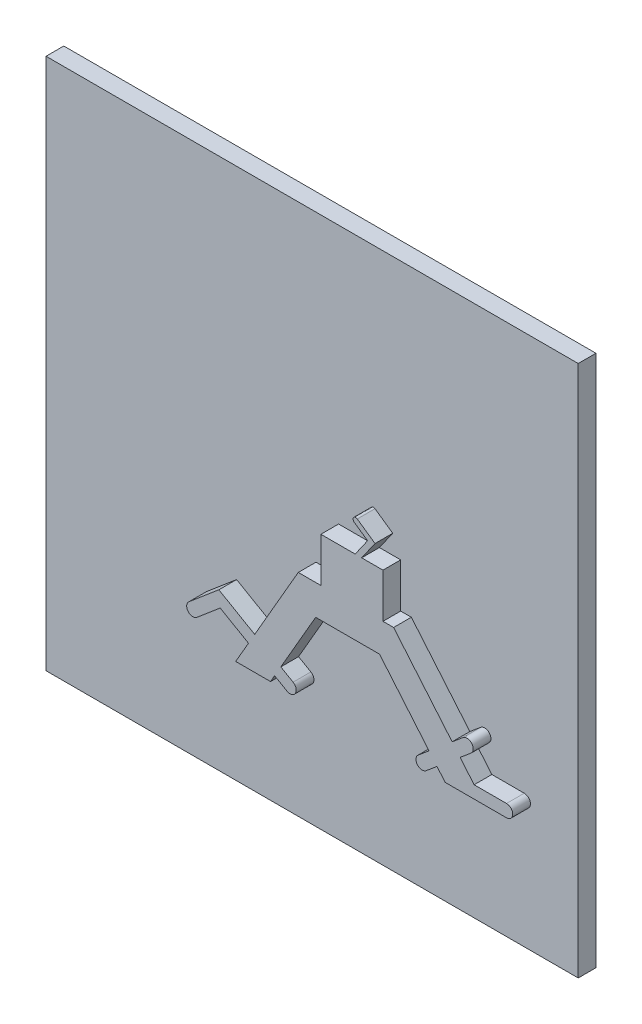
SolidWorks part; units mm, degrees
material "Obyčejná uhlíková ocel"
ref_plane "Přední rovina" through (0, 0, 0) normal (0, 0, 1) x (1, 0, 0)
ref_plane "Horní rovina" through (0, 0, 0) normal (0, 1, 0) x (1, 0, 0)
ref_plane "Pravá rovina" through (0, 0, 0) normal (1, 0, 0) x (0, 0, -1)
sketch "Skica1" plane through (0, 0, 0) normal (0, 0, 1) x (1, 0, 0)
  line L1 (0, 0) -> (300, 0)
  line L2 (0, 0) -> (0, 300)
  line L3 (0, 300) -> (300, 300)
  line L4 (300, 0) -> (300, 300)
  dimension "D1" = 300
extrude "Přidat vysunutím1" add sketch "Skica1" along normal blind 10
sketch "Skica3" plane through (0, 0, 10) normal (0, 0, 1) x (1, 0, 0)
  line L33 (116.9119, 68) -> (124.1266, 80.4961)
  line L35 (152.185, 129.0949) -> (164.9272, 129.0949)
  line L36 (205.9272, 129.0949) -> (238.9179, 89.7781)
  line L38 (235, 68) -> (230.3947, 73.4884)
  line L39 (198, 112.0949) -> (162, 112.0949)
  line L40 (162, 112.0949) -> (142.349, 78.0583)
  line L41 (136.5418, 68) -> (116.9119, 68)
  line L42 (187.9272, 154.0949) -> (195.4452, 164.8316)
  line L44 (164.9272, 129.0949) -> (164.9272, 154.0949)
  line L45 (164.9272, 154.0949) -> (184.2649, 154.0949)
  line L46 (199.9272, 129.0949) -> (199.9272, 154.0949)
  line L47 (195.4452, 164.8316) -> (185.4452, 171.8337)
  line L49 (183.7244, 169.3762) -> (191.267, 164.0949)
  line L50 (191.267, 164.0949) -> (184.2649, 154.0949)
  line L51 (108.1805, 89.7026) -> (124.1266, 80.4961)
  line L53 (149.2772, 74.0583) -> (142.349, 78.0583)
  line L54 (107.416, 98.2269) -> (90.515, 83.9192)
  line L56 (95.0378, 78.5766) -> (108.1805, 89.7026)
  line L58 (224.2663, 68.3461) -> (230.3947, 73.4884)
  line L60 (245.0463, 94.9204) -> (238.9179, 89.7781)
  line L61 (138.849, 71.9961) -> (145.7772, 67.9961)
  line L62 (127.6266, 86.5583) -> (107.416, 98.2269)
  line L63 (127.6266, 86.5583) -> (152.185, 129.0949)
  line L64 (138.849, 71.9961) -> (136.5418, 68)
  line L65 (225.8952, 78.8507) -> (219.7668, 73.7084)
  line L66 (243.4175, 84.4158) -> (249.5458, 89.5581)
  line L67 (243.4175, 84.4158) -> (251.3182, 75)
  line L68 (225.8952, 78.8507) -> (198, 112.0949)
  line L69 (300, 0) -> (300, 300) construction
  line L70 (180, 112.0949) -> (180, 49.7513) construction
  line L72 (251.3182, 75) -> (269.5798, 75)
  line L73 (269.5798, 68) -> (235, 68)
  line L74 (0, 0) -> (300, 0) construction
  line L75 (187.9272, 154.0949) -> (199.9272, 154.0949)
  line L76 (199.9272, 129.0949) -> (205.9272, 129.0949)
  arc A54 (245.0463, 94.9204) -> (249.5458, 89.5581) centre (247.2961, 92.2392) cw
  arc A55 (219.7668, 73.7084) -> (224.2663, 68.3461) centre (222.0166, 71.0272) ccw
  arc A56 (269.5798, 75) -> (269.5798, 68) centre (269.5798, 71.5) cw
  arc A57 (149.2772, 74.0583) -> (145.7772, 67.9961) centre (147.5272, 71.0272) cw
  arc A58 (95.0378, 78.5766) -> (90.515, 83.9192) centre (92.7764, 81.2479) cw
  arc A59 (183.7244, 169.3762) -> (185.4452, 171.8337) centre (184.5848, 170.605) cw
  point P37 (180, 112.0949)
  point P53 (0, 0)
  dimension "D1" = 120
  dimension "D2" = 30
  dimension "D3" = 40
  dimension "D4" = 17
  dimension "D5" = 17
  dimension "D6" = 17
  dimension "D7" = 68
  dimension "D8" = 7
  dimension "D9" = 36
  dimension "D10" = 8
  dimension "D11" = 8
  dimension "D12" = 7
  dimension "D13" = 65
  dimension "D14" = 34.5798
  dimension "D15" = 10
  dimension "D16" = 3
  dimension "D17" = 3
  dimension "D18" = 7
  dimension "D19" = 8
  dimension "D20" = 7
  dimension "D21" = 25
  dimension "D22" = 55
  dimension "D23" = 6
  dimension "D24" = 35
  dimension "D25" = 12
  dimension "D26" = 10
extrude "Přidat vysunutím3" add sketch "Skica3" along normal blind 10
